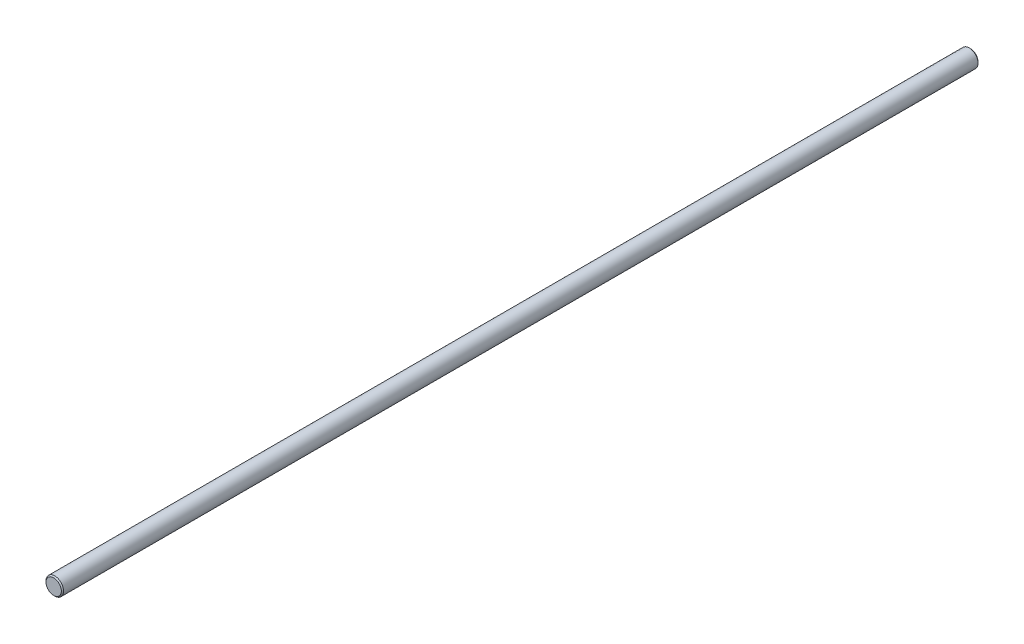
SolidWorks part; units mm, degrees
ref_plane "Front Plane" through (0, 0, 0) normal (0, 0, 1) x (1, 0, 0)
ref_plane "Top Plane" through (0, 0, 0) normal (0, 1, 0) x (1, 0, 0)
ref_plane "Right Plane" through (0, 0, 0) normal (1, 0, 0) x (0, 0, -1)
ref_plane "Plane1" through (0, 0, 0) normal (0, -1, 0) x (1, 0, 0)
sketch "Sketch1" plane through (0, 0, 0) normal (0, -1, 0) x (1, 0, 0)
  line L0 (3.5, 418) -> (0, 418)
  line L1 (0, 418) -> (0, 0)
  line L2 (0, 0) -> (3.5, 0)
  line L3 (3.5, 0) -> (4, 0.5)
  line L4 (4, 0.5) -> (4, 417.5)
  line L5 (4, 417.5) -> (3.5, 418)
  line L6 (0, 418) -> (0, 0) construction
revolve "Revolve1" add sketch "Sketch1" angle 360 about L6
